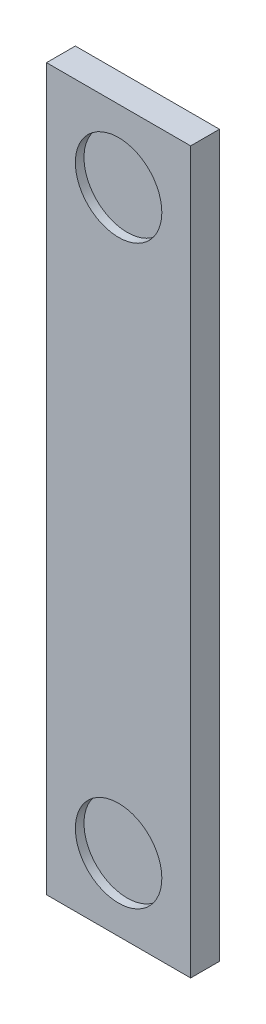
SolidWorks part; units mm, degrees
material "Plain Carbon Steel"
ref_plane "Front Plane" through (0, 0, 0) normal (0, 0, 1) x (1, 0, 0)
ref_plane "Top Plane" through (0, 0, 0) normal (0, 1, 0) x (1, 0, 0)
ref_plane "Right Plane" through (0, 0, 0) normal (1, 0, 0) x (0, 0, -1)
sketch "Sketch1" plane through (0, 0, 0) normal (0, 0, 1) x (1, 0, 0)
  line L1 (-25, 125) -> (25, 125)
  line L2 (-25, 125) -> (-25, -125)
  line L3 (-25, -125) -> (25, -125)
  line L4 (25, 125) -> (25, -125)
  line L5 (-25, 125) -> (25, -125) construction
  line L6 (-25, -125) -> (25, 125) construction
  point P0 (0, 0)
  dimension "D1" = 50
  dimension "D2" = 250
extrude "Boss-Extrude1" add sketch "Sketch1" along normal mid plane 10
sketch "Sketch2" plane through (0, 0, 5) normal (0, 0, 1) x (1, 0, 0)
  line L0 (-25, -125) -> (25, -125) construction
  line L1 (25, 125) -> (-25, 125) construction
  circle A0 centre (0, 100) radius 15
  circle A1 centre (0, -100) radius 15
  dimension "D2" = 25
  dimension "D3" = 30
  dimension "D4" = 30
  dimension "D1" = 25
extrude "Cut-Extrude1" cut sketch "Sketch2" against normal blind 3
sketch "Sketch3" plane through (0, 0, 2) normal (0, 0, 1) x (1, 0, 0)
  point P0 (0, 100)
  point P1 (0, -100)
sketch "Sketch4" plane through (0, 0, 0) normal (0, 0, 1) x (1, 0, 0)
  line L0 (0, 148.3761) -> (0, -149.1929) construction
